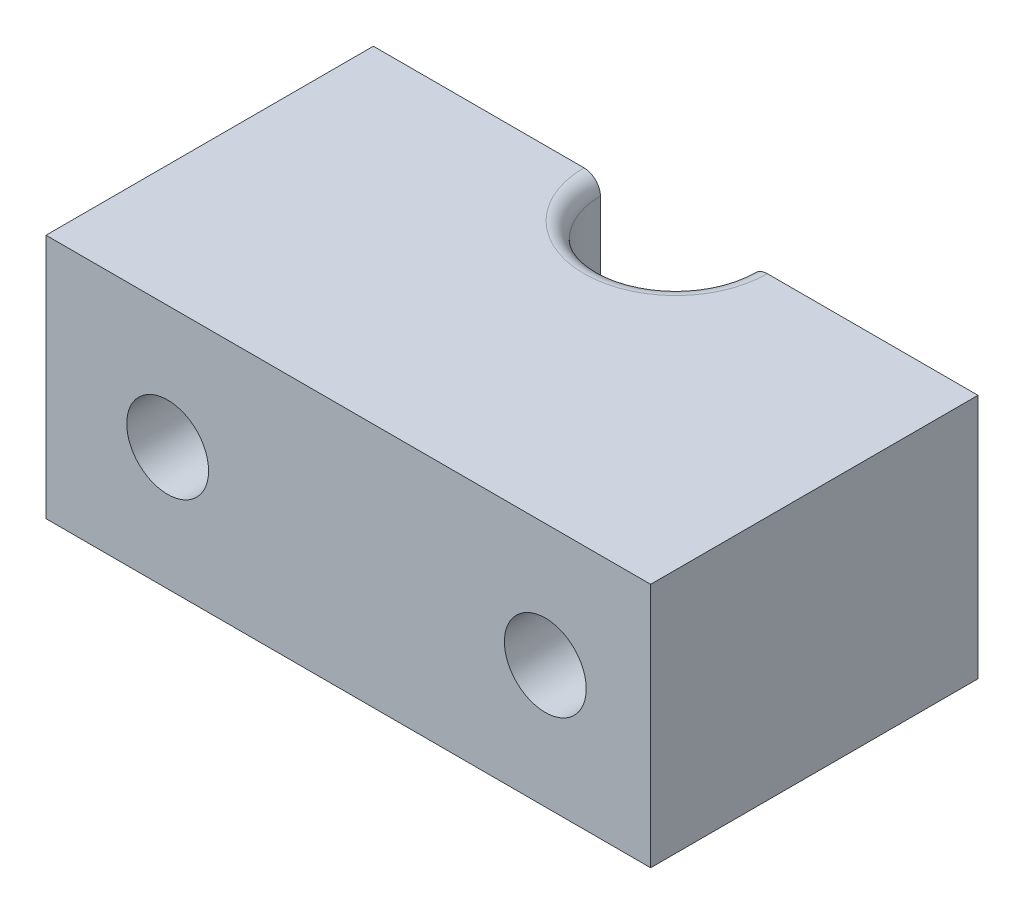
SolidWorks part; units mm, degrees
ref_plane "前基準面" through (0, 0, 0) normal (0, 0, 1) x (1, 0, 0)
ref_plane "上基準面" through (0, 0, 0) normal (0, 1, 0) x (1, 0, 0)
ref_plane "右基準面" through (0, 0, 0) normal (1, 0, 0) x (0, 0, -1)
sketch "草圖1" plane through (0, 0, 0) normal (0, 1, 0) x (1, 0, 0)
  line L1 (0, 0) -> (125, 0)
  line L2 (0, 0) -> (0, 40)
  line L3 (0, 40) -> (125, 40)
  line L4 (125, 0) -> (125, 40)
  dimension "D1" = 125
  dimension "D2" = 40
extrude "填料-伸長1" add sketch "草圖1" along normal blind 15
sketch "草圖2" plane through (0, 15, 0) normal (0, 1, 0) x (1, 0, 0)
  line L0 (-4.3311, 20) -> (135.7424, 20) construction
  line L1 (0, 0) -> (125, 0) construction
  line L2 (125, 40) -> (0, 40) construction
  line L3 (0, 40) -> (0, 0) construction
  circle A0 centre (18.5267, 20) radius 8.9
  circle A1 centre (106.5267, 20) radius 4.6
  circle A2 centre (62.5267, 20) radius 13.3
  dimension "D1" = 26.6
  dimension "D2" = 9.2
  dimension "D3" = 17.8
  dimension "D4" = 44
  dimension "D5" = 44
  dimension "D6" = 18.5267
extrude "除料-伸長1" cut sketch "草圖2" against normal through all
chamfer "導角1" distance 1 angle 45 1 edges at (18.5267, 15, -11.1)
chamfer "導角2" distance 1 angle 45 1 edges at (18.5267, 0, -11.1)
fillet "圓角1" radius 1 4 edges at (62.5267, 0, -6.7) (106.5267, 0, -15.4) (106.5267, 15, -15.4) (62.5267, 15, -6.7)
sketch "草圖5" plane through (0, 15, 0) normal (0, 1, 0) x (1, 0, 0)
  line L0 (85, 20) -> (125, 20)
  line L1 (125, 0) -> (85, 0)
  line L2 (125, 0) -> (125, 20)
  line L4 (85, 0) -> (85, 20)
  dimension "D1" = 40
extrude "除料-伸長2" cut sketch "草圖5" against normal through all
fillet "圓角4" radius 5 2 edges at (0, 7.5, -40) (0, 7.5, 0)
sketch "草圖12" plane through (0, 15, 0) normal (0, 1, 0) x (1, 0, 0)
  line L0 (5, 0) -> (85, 0) construction
  line L1 (85, 20) -> (88.06, 20)
  line L2 (85, 20) -> (85, 0)
  line L3 (85, 0) -> (88.06, 0)
  line L4 (88.06, 20) -> (88.06, 0)
  dimension "D1" = 3.06
extrude "填料-伸長2" add sketch "草圖12" against normal up to surface (15 mm away) up to face at (64.0982, 0, -20.56)
sketch "草圖14" plane through (0, 0, -20) normal (0, 0, 1) x (1, 0, 0)
  line L0 (100.9267, 0) -> (88.06, 0) construction
  line L1 (125, 0) -> (112.1267, 0) construction
  line L3 (125, 0) -> (125, 15) construction
  line L4 (101.9267, 14) -> (101.9267, 1) construction
  circle A0 centre (118.565, 7.5) radius 2.5
  circle A1 centre (95.4917, 7.5) radius 2.5
  dimension "D1" = 5
  dimension "D2" = 5
  dimension "D5" = 6.435
  dimension "D3" = 7.5
  dimension "D4" = 7.5
  dimension "D6" = 6.435
extrude "除料-伸長3" cut sketch "草圖14" against normal through all
sketch "草圖15" plane through (0, 15, 0) normal (0, 1, 0) x (1, 0, 0)
  line L1 (125, 0) -> (88.06, 0)
  line L2 (125, 0) -> (125, 20)
  line L3 (125, 20) -> (88.06, 20)
  line L4 (88.06, 0) -> (88.06, 20)
extrude "填料-伸長3" add sketch "草圖15" against normal blind 15 separate body
sketch "草圖16" plane through (0, 15, 0) normal (0, 1, 0) x (1, 0, 0)
  line L1 (88.06, 0) -> (-18.3654, 0)
  line L2 (88.06, 0) -> (88.06, 56.3369)
  line L3 (88.06, 56.3369) -> (-18.3654, 56.3369)
  line L4 (-18.3654, 0) -> (-18.3654, 56.3369)
extrude "除料-伸長4" cut sketch "草圖16" against normal through all
sketch "草圖17" plane through (0, 0, 0) normal (0, 0, 1) x (1, 0, 0)
  circle A1 centre (95.4917, 7.5) radius 2.5
  circle A2 centre (95.4917, 7.5) radius 2.5
  circle A3 centre (118.565, 7.5) radius 2.5
  circle A4 centre (118.565, 7.5) radius 2.5
  dimension "D1" = 0
  dimension "D2" = 0
extrude "除料-伸長5" cut sketch "草圖17" against normal through all
sketch "草圖18" plane through (0, 15, 0) normal (0, 1, 0) x (1, 0, 0)
  line L0 (125, 20) -> (88.06, 20) construction
  circle A0 centre (106.53, 20) radius 4.6
  dimension "D1" = 9.2
extrude "除料-伸長6" cut sketch "草圖18" against normal through all
fillet "圓角5" radius 1 1 edges at (106.53, 15, -15.4)
sketch "草圖19" plane through (0, 15, 0) normal (0, 1, 0) x (1, 0, 0)
  line L1 (88.06, 20) -> (135.4368, 20)
  line L2 (88.06, 20) -> (88.06, 42.0063)
  line L3 (88.06, 42.0063) -> (135.4368, 42.0063)
  line L4 (135.4368, 20) -> (135.4368, 42.0063)
extrude "除料-伸長7" cut sketch "草圖19" against normal through all
fillet "圓角6" radius 1 1 edges at (106.53, 0, -15.4)
